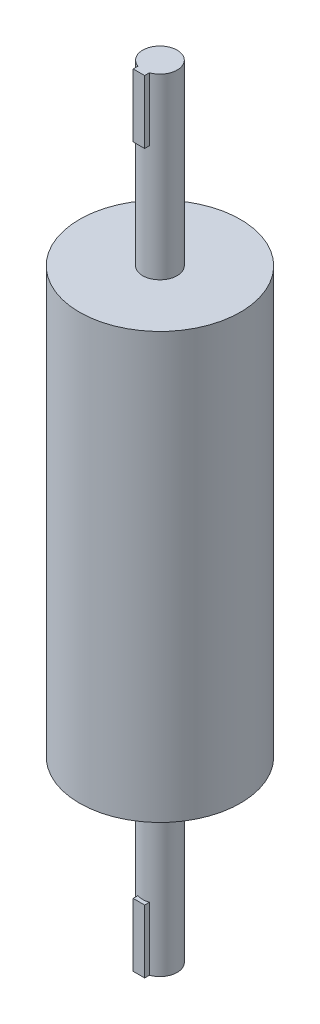
SolidWorks part; units mm, degrees
material "1023 Carbon Steel Sheet (SS)"
ref_plane "Front Plane" through (0, 0, 0) normal (0, 0, 1) x (1, 0, 0)
ref_plane "Top Plane" through (0, 0, 0) normal (0, 1, 0) x (1, 0, 0)
ref_plane "Right Plane" through (0, 0, 0) normal (1, 0, 0) x (0, 0, -1)
sketch "Sketch1" plane through (0, 0, 0) normal (0, 1, 0) x (1, 0, 0)
  circle A0 centre (0, 0) radius 70
extrude "Boss-Extrude1" add sketch "Sketch1" along normal blind 370
sketch "Sketch2" plane through (0, 370, 0) normal (0, 1, 0) x (1, 0, 0)
  circle A0 centre (0, 0) radius 10
extrude "Boss-Extrude2" add sketch "Sketch2" along normal blind 100
sketch "Sketch3" plane through (0, 0, 0) normal (0, -1, 0) x (1, 0, 0)
  circle A0 centre (0, 0) radius 10
extrude "Boss-Extrude3" add sketch "Sketch3" along normal blind 100
sketch "Sketch4" plane through (0, 470, 0) normal (0, 1, 0) x (1, 0, 0)
  line L0 (0, 10) -> (-5, 10) construction
  line L1 (0, 10) -> (5, 10) construction
  line L2 (-5, 8.6603) -> (-5, 12.8203)
  line L3 (-5, 12.8203) -> (5, 12.8203)
  line L4 (5, 12.8203) -> (5, 8.6603)
  circle A0 centre (0, 0) radius 10 construction
  circle A1 centre (0, 0) radius 10 construction
  arc A2 (5, 8.6603) -> (-5, 8.6603) centre (0, 0) ccw
extrude "Boss-Extrude4" add sketch "Sketch4" against normal blind 25
sketch "Sketch5" plane through (0, -100, 0) normal (0, -1, 0) x (1, 0, 0)
  line L0 (0, 10) -> (5, 10) construction
  line L1 (0, 10) -> (-5, 10) construction
  line L2 (-5, 8.6603) -> (-5, 12.8203)
  line L3 (-5, 12.8203) -> (5, 12.8203)
  line L4 (5, 12.8203) -> (5, 8.6603)
  circle A0 centre (0, 0) radius 10 construction
  circle A1 centre (0, 0) radius 10 construction
  arc A2 (5, 8.6603) -> (-5, 8.6603) centre (0, 0) ccw
extrude "Boss-Extrude5" add sketch "Sketch5" against normal blind 25
sketch "Sketch6" plane through (0, -100, 0) normal (0, -1, 0) x (1, 0, 0)
  circle A0 centre (0, 0) radius 15
extrude "Boss-Extrude6" add sketch "Sketch6" against normal blind 570
sketch "Sketch7" plane through (0, -100, 0) normal (0, -1, 0) x (1, 0, 0)
  circle A0 centre (0, 0) radius 15
extrude "Boss-Extrude7" add sketch "Sketch7" along normal blind 55
sketch "Sketch8" plane through (0, 470, 0) normal (0, 1, 0) x (1, 0, 0)
  circle A0 centre (0, 0) radius 15
extrude "Boss-Extrude8" add sketch "Sketch8" along normal blind 55
sketch "Sketch9" plane through (0, -155, 0) normal (0, -1, 0) x (1, 0, 0)
  line L0 (0, 15) -> (5, 15) construction
  line L1 (0, 15) -> (-5, 15) construction
  line L2 (-5, 14.1421) -> (-5, 18.3021)
  line L3 (-5, 18.3021) -> (5, 18.3021)
  line L4 (5, 18.3021) -> (5, 14.1421)
  circle A0 centre (0, 0) radius 15 construction
  circle A1 centre (0, 0) radius 15 construction
  arc A2 (5, 14.1421) -> (-5, 14.1421) centre (0, 0) ccw
extrude "Boss-Extrude9" add sketch "Sketch9" against normal blind 55
sketch "Sketch10" plane through (0, 525, 0) normal (0, 1, 0) x (1, 0, 0)
  line L0 (0, -15) -> (5, -15) construction
  line L1 (0, -15) -> (-5, -15) construction
  line L2 (5, -14.1421) -> (5, -18.3021)
  line L3 (5, -18.3021) -> (-5, -18.3021)
  line L4 (-5, -18.3021) -> (-5, -14.1421)
  circle A0 centre (0, 0) radius 15 construction
  circle A1 centre (0, 0) radius 15 construction
  arc A2 (-5, -14.1421) -> (5, -14.1421) centre (0, 0) ccw
extrude "Boss-Extrude10" add sketch "Sketch10" against normal blind 55
